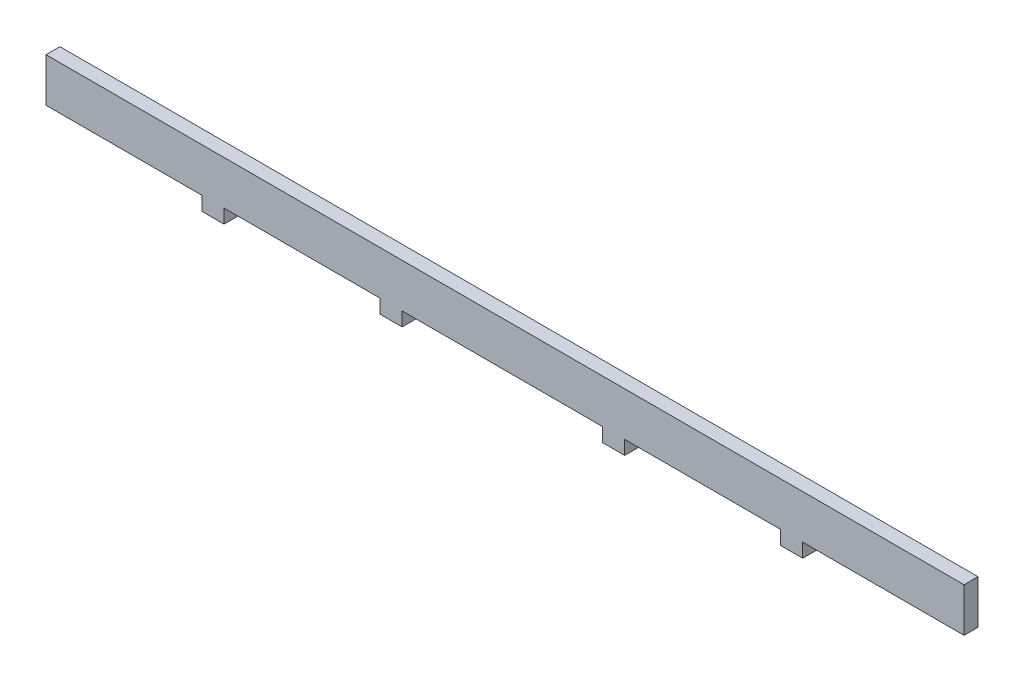
SolidWorks part; units mm, degrees
ref_plane "Front Plane" through (0, 0, 0) normal (0, 0, 1) x (1, 0, 0)
ref_plane "Top Plane" through (0, 0, 0) normal (0, 1, 0) x (1, 0, 0)
ref_plane "Right Plane" through (0, 0, 0) normal (1, 0, 0) x (0, 0, -1)
sketch "Sketch1" plane through (0, 0, 0) normal (0, 0, 1) x (1, 0, 0)
  line L0 (-2.2672, 60.1068) -> (-2.2672, 56.9318)
  line L1 (-129.2672, 70.1068) -> (80.2828, 70.1068)
  line L2 (-129.2672, 70.1068) -> (-129.2672, 60.1068)
  line L3 (-129.2672, 60.1068) -> (-93.7072, 60.1068)
  line L4 (80.2828, 70.1068) -> (80.2828, 60.1068)
  line L5 (-47.9872, 60.1068) -> (-2.2672, 60.1068)
  line L6 (-93.7072, 60.1068) -> (-93.7072, 56.9318)
  line L7 (-93.7072, 56.9318) -> (-88.6272, 56.9318)
  line L8 (-88.6272, 60.1068) -> (-88.6272, 56.9318)
  line L9 (2.8128, 60.1068) -> (38.3728, 60.1068)
  line L10 (-53.0672, 60.1068) -> (-53.0672, 56.9318)
  line L11 (-53.0672, 56.9318) -> (-47.9872, 56.9318)
  line L12 (-47.9872, 60.1068) -> (-47.9872, 56.9318)
  line L13 (-2.2672, 56.9318) -> (2.8128, 56.9318)
  line L14 (2.8128, 60.1068) -> (2.8128, 56.9318)
  line L15 (38.3728, 60.1068) -> (38.3728, 56.9318)
  line L16 (38.3728, 56.9318) -> (43.4528, 56.9318)
  line L17 (43.4528, 60.1068) -> (43.4528, 56.9318)
  line L18 (-88.6272, 60.1068) -> (-53.0672, 60.1068)
  line L19 (43.4528, 60.1068) -> (80.2828, 60.1068)
  dimension "D1" = 209.55
  dimension "D2" = 10
  dimension "D3" = 35.56
  dimension "D4" = 5.08
  dimension "D5" = 3.175
  dimension "D6" = 35.56
  dimension "D7" = 5.08
  dimension "D8" = 3.175
extrude "Boss-Extrude1" add sketch "Sketch1" along normal blind 3.175
